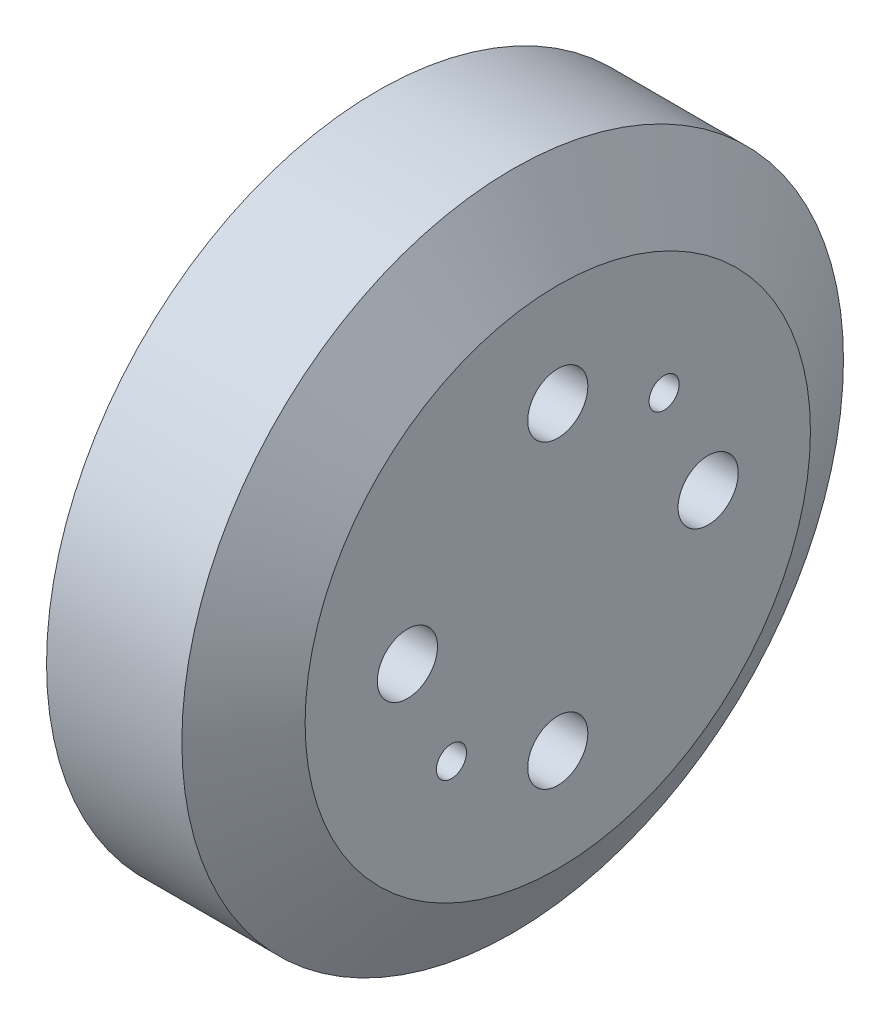
SolidWorks part; units mm, degrees
ref_plane "Front Plane" through (0, 0, 0) normal (0, 0, 1) x (1, 0, 0)
ref_plane "Top Plane" through (0, 0, 0) normal (0, 1, 0) x (1, 0, 0)
ref_plane "Right Plane" through (0, 0, 0) normal (1, 0, 0) x (0, 0, -1)
sketch "Sketch1" plane through (0, 0, 0) normal (1, 0, 0) x (0, 0, -1)
  circle A0 centre (0, 0) radius 110
  circle A1 centre (0, 0) radius 100
  dimension "D1" = 220
  dimension "D2" = 200
extrude "Boss-Extrude1" add sketch "Sketch1" along normal blind 45
sketch "Sketch2" plane through (45, 0, 0) normal (1, 0, 0) x (0, 0, -1)
  circle A0 centre (0, 0) radius 110
extrude "Boss-Extrude2" add sketch "Sketch2" along normal blind 15 draft 60
sketch "Sketch3" plane through (45, 0, 0) normal (-1, 0, 0) x (0, 0, 1)
  circle A0 centre (0, 0) radius 30
extrude "Boss-Extrude3" add sketch "Sketch3" along normal blind 100
sketch "Sketch4" plane through (60, 0, 0) normal (1, 0, 0) x (0, 0, -1)
  line L0 (0, 50) -> (35.3553, 35.3553) construction
  line L1 (35.3553, 35.3553) -> (50, 0) construction
  circle A0 centre (0, 0) radius 50 construction
  circle A1 centre (0, 50) radius 10
  circle A2 centre (50, 0) radius 10
  circle A3 centre (0, -50) radius 10
  circle A4 centre (-50, 0) radius 10
  circle A5 centre (35.3553, 35.3553) radius 5
  circle A6 centre (-35.3553, -35.3553) radius 5
  point P14 (0, 0)
  point P16 (0, 0)
  point P20 (0, 0)
  dimension "D1" = 4
  dimension "D2" = 100
  dimension "D3" = 20
  dimension "D7" = 2
  dimension "D6" = 10
  dimension "D4" = 50
  dimension "D5" = 50
  dimension "D8" = 100
  dimension "D9" = 50
extrude "Cut-Extrude1" cut sketch "Sketch4" against normal blind 100
